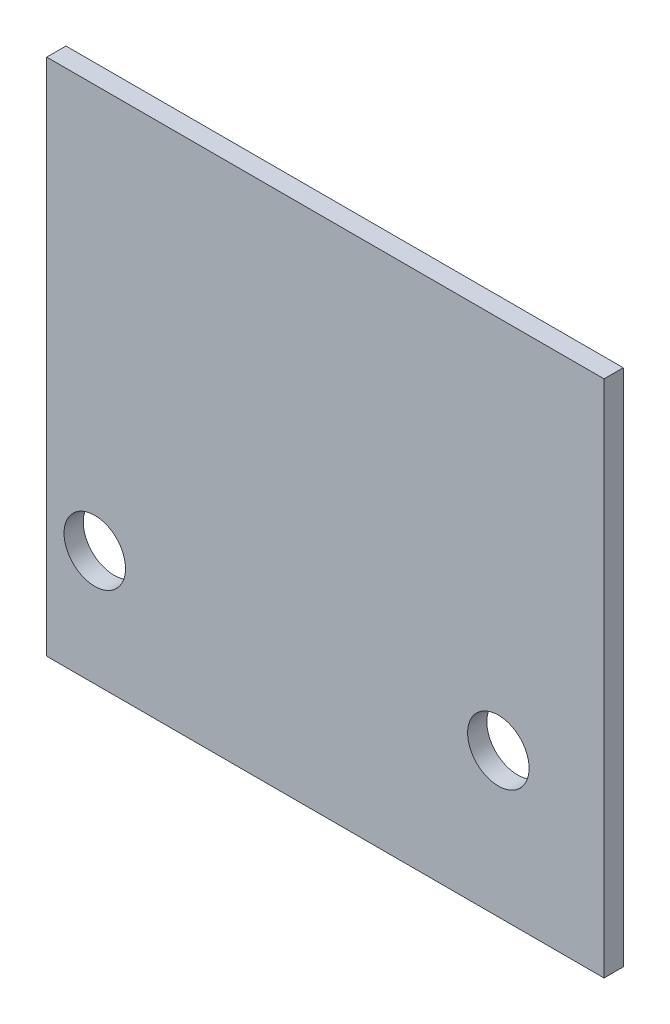
SolidWorks part; units mm, degrees
ref_plane "Front Plane" through (0, 0, 0) normal (0, 0, 1) x (1, 0, 0)
ref_plane "Top Plane" through (0, 0, 0) normal (0, 1, 0) x (1, 0, 0)
ref_plane "Right Plane" through (0, 0, 0) normal (1, 0, 0) x (0, 0, -1)
sketch "Sketch1" plane through (0, 0, 0) normal (0, 0, 1) x (1, 0, 0)
  line L1 (-14.5, -13.5) -> (14.5, -13.5)
  line L2 (-14.5, -13.5) -> (-14.5, 13.5)
  line L3 (-14.5, 13.5) -> (14.5, 13.5)
  line L4 (14.5, -13.5) -> (14.5, 13.5)
  line L5 (-14.5, -13.5) -> (14.5, 13.5) construction
  line L6 (-14.5, 13.5) -> (14.5, -13.5) construction
  point P0 (0, 0)
  dimension "D1" = 27
  dimension "D2" = 29
extrude "Boss-Extrude1" add sketch "Sketch1" along normal blind 1
sketch "Sketch2" plane through (0, 0, 1) normal (0, 0, 1) x (1, 0, 0)
  line L0 (14.5, -13.5) -> (14.5, 13.5) construction
  line L1 (-14.5, -13.5) -> (14.5, -13.5) construction
  circle A0 centre (9, -6) radius 1.6
  circle A1 centre (-12, -7.5) radius 1.6
  point P4 (0, 0)
  point P5 (0.5019, 12.5592)
  point P8 (2, -9.461)
  point P9 (9, 9.6483)
  point P10 (-12, 8.8839)
  point P11 (9, -8.429)
  point P14 (-12, -8.7279)
  point P15 (0, 0)
  dimension "D1" = 7.5
  dimension "D2" = 3.2
  dimension "D4" = 5.5
  dimension "D3" = 21
  dimension "D5" = 6
extrude "Cut-Extrude1" cut sketch "Sketch2" against normal through all contours A0 | A1
